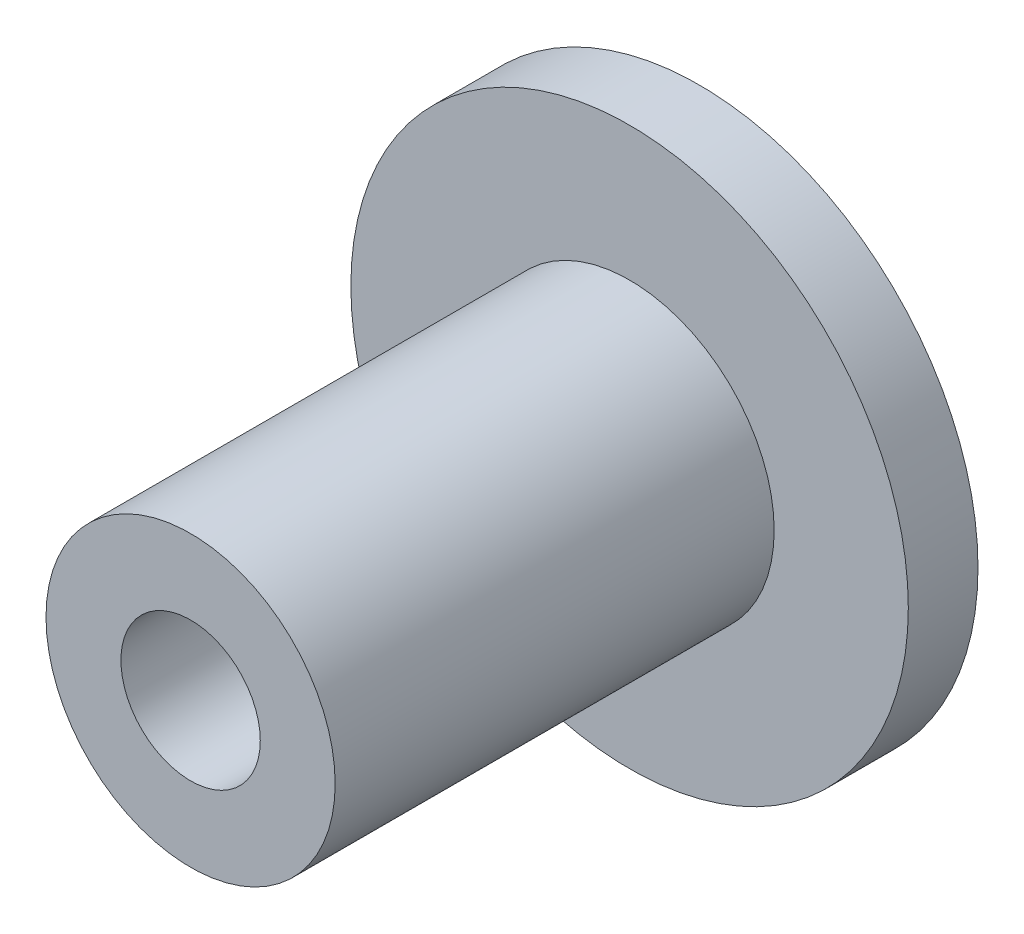
SolidWorks part; units mm, degrees
material "ABS"
ref_plane "Front Plane" through (0, 0, 0) normal (0, 0, 1) x (1, 0, 0)
ref_plane "Top Plane" through (0, 0, 0) normal (0, 1, 0) x (1, 0, 0)
ref_plane "Right Plane" through (0, 0, 0) normal (1, 0, 0) x (0, 0, -1)
sketch "Flange Sketch" plane through (0, 0, 0) normal (0, 0, 1) x (1, 0, 0)
  circle A0 centre (0, 0) radius 4
  dimension "D1" = 8
extrude "Flange Extrude" add sketch "Flange Sketch" along normal mid plane 1
sketch "Joint Sketch" plane through (0, 0, 0.5) normal (0, 0, 1) x (1, 0, 0)
  circle A0 centre (0, 0) radius 2.075
  dimension "D1" = 4.15
extrude "Joint Extrude" add sketch "Joint Sketch" along normal blind 6.3
sketch "Hole Sketch" plane through (0, 0, 6.8) normal (0, 0, 1) x (1, 0, 0)
  circle A0 centre (0, 0) radius 1
  dimension "D1" = 2
extrude "Hole Extrude" cut sketch "Hole Sketch" against normal through all
equation "\"Joint Diameter\"= 4.15"
equation "\"Flange Diameter\"= 8"
equation "\"Bolt Diameter\"= 2"
equation "\"Joint Length\"= 6.3"
equation "\"Flange Length\"= 1"
equation "\"D1@Flange Sketch\" = \"Flange Diameter\""
equation "\"D1@Flange Extrude\" = \"Flange Length\""
equation "\"D1@Joint Sketch\" = \"Joint Diameter\""
equation "\"D1@Joint Extrude\" = \"Joint Length\""
equation "\"D1@Hole Sketch\" = \"Bolt Diameter\""
